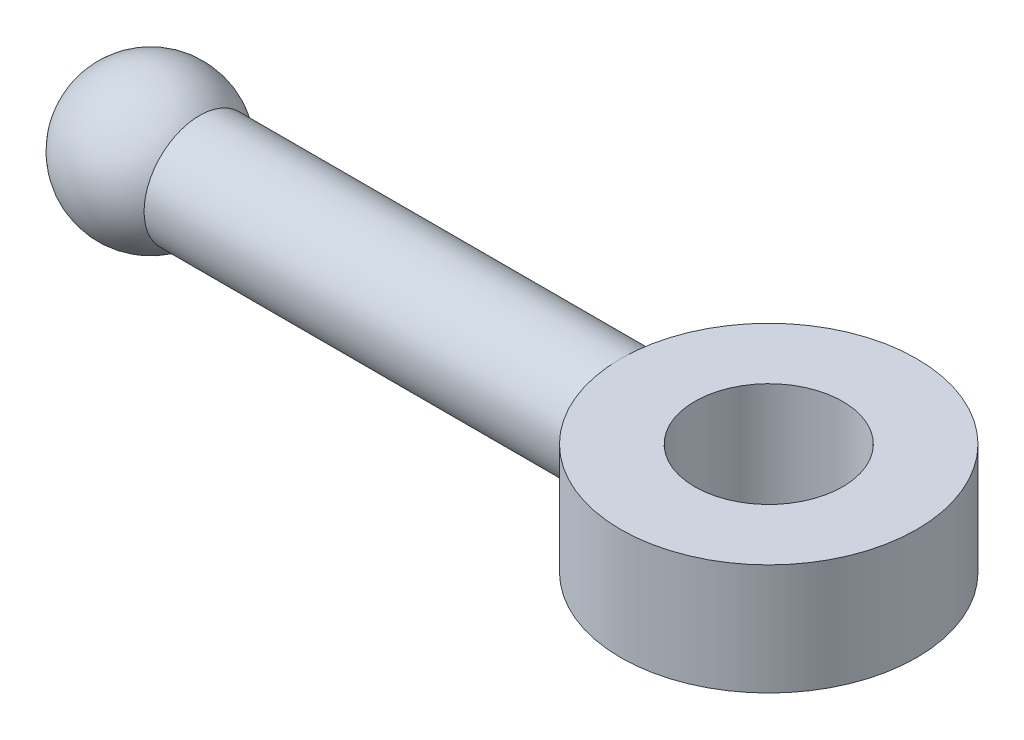
SolidWorks part; units mm, degrees
ref_plane "Front Plane" through (0, 0, 0) normal (0, 0, 1) x (1, 0, 0)
ref_plane "Top Plane" through (0, 0, 0) normal (0, 1, 0) x (1, 0, 0)
ref_plane "Right Plane" through (0, 0, 0) normal (1, 0, 0) x (0, 0, -1)
sketch "Sketch1" plane through (0, 0, 0) normal (1, 0, 0) x (0, 0, -1)
  circle A0 centre (0, 0) radius 15
  dimension "D1" = 30
extrude "Boss-Extrude1" add sketch "Sketch1" along normal blind 130
ref_plane "Plane1" through (131.016, 0, 0) normal (1, 0, 0) x (0, 0, -1)
sketch "Sketch4" plane through (0, 0, 0) normal (0, 0, 1) x (1, 0, 0)
  line L0 (0, 15) -> (0, -15) construction
  line L1 (-20, 0) -> (20, 0)
  line L2 (0, 0) -> (46.2038, 0) construction
  arc A0 (20, 0) -> (-20, 0) centre (0, 0) ccw
  dimension "D1" = 40
revolve "Revolve1" add sketch "Sketch4" angle 360 about L2
ref_plane "Plane2" through (81, 0, 0) normal (1, 0, 0) x (0, 0, -1)
sketch "Sketch7" plane through (0, 0, 0) normal (0, 1, 0) x (1, 0, 0)
  circle A0 centre (167.081, 0) radius 40
  circle A1 centre (167.081, 0) radius 20
  dimension "D1" = 80
  dimension "D2" = 40
extrude "Boss-Extrude2" add sketch "Sketch7" along normal mid plane 30 contours A0
